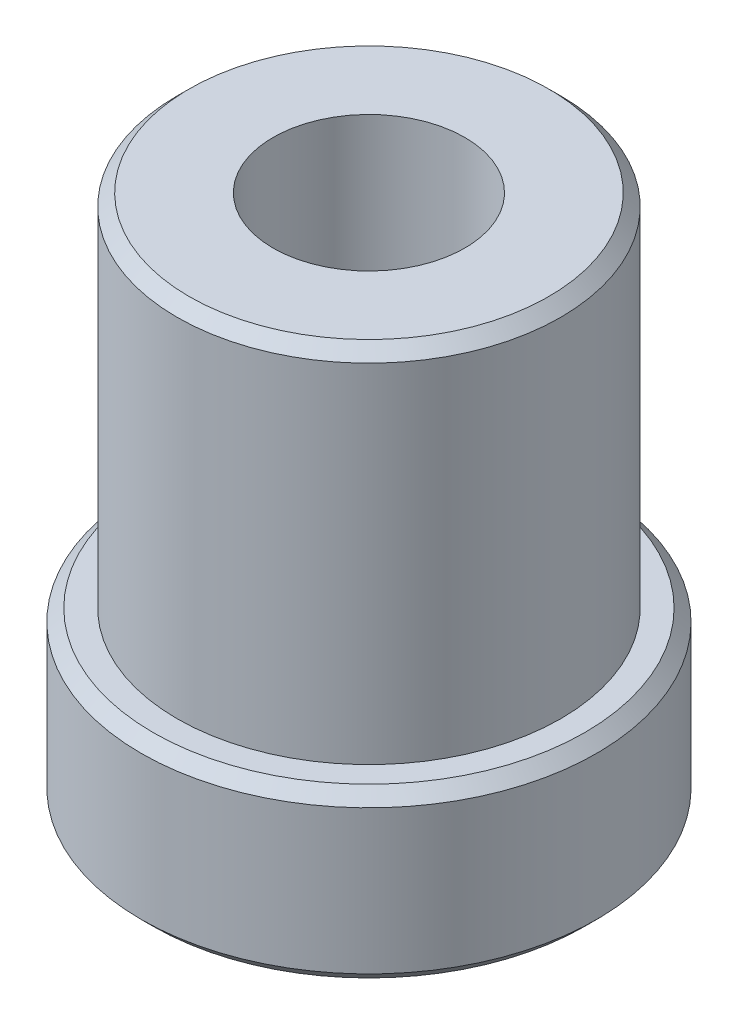
SolidWorks part; units mm, degrees
material "Brass"
ref_plane "Front Plane" through (0, 0, 0) normal (0, 0, 1) x (1, 0, 0)
ref_plane "Top Plane" through (0, 0, 0) normal (0, 1, 0) x (1, 0, 0)
ref_plane "Right Plane" through (0, 0, 0) normal (1, 0, 0) x (0, 0, -1)
sketch "Sketch1" plane through (0, 0, 0) normal (0, 1, 0) x (1, 0, 0)
  circle A0 centre (0, 0) radius 9.5
  dimension "D1" = 19
extrude "Boss-Extrude1" add sketch "Sketch1" along normal blind 7
sketch "Sketch2" plane through (0, 7, 0) normal (0, 1, 0) x (1, 0, 0)
  circle A0 centre (0, 0) radius 8
extrude "Boss-Extrude2" add sketch "Sketch2" along normal blind 15
sketch "Sketch3" plane through (0, 22, 0) normal (0, 1, 0) x (1, 0, 0)
  circle A0 centre (0, 0) radius 4
extrude "Cut-Extrude1" cut sketch "Sketch3" against normal through all
chamfer "Chamfer1" distance 0.5 angle 45 3 edges at (0, 0, 9.5) (0, 7, 9.5) (0, 22, 8)
